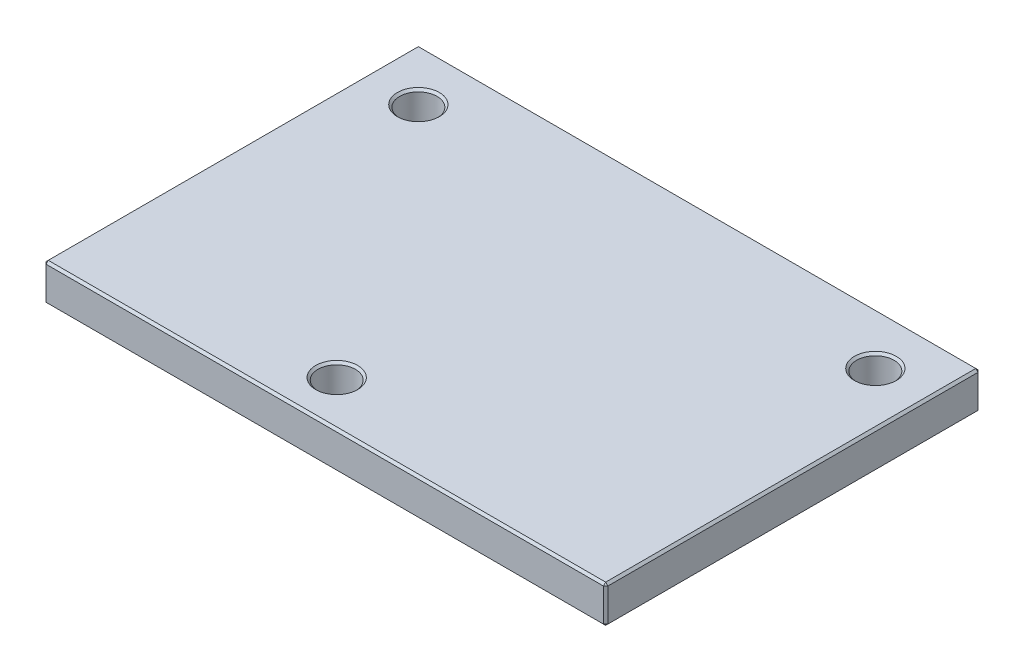
SolidWorks part; units mm, degrees
material "Plain Carbon Steel"
ref_plane "Front Plane" through (0, 0, 0) normal (0, 0, 1) x (1, 0, 0)
ref_plane "Top Plane" through (0, 0, 0) normal (0, 1, 0) x (1, 0, 0)
ref_plane "Right Plane" through (0, 0, 0) normal (1, 0, 0) x (0, 0, -1)
sketch "Sketch1" plane through (0, 0, 0) normal (0, 1, 0) x (1, 0, 0)
  line L1 (-375, -250) -> (375, -250)
  line L2 (-375, -250) -> (-375, 250)
  line L3 (-375, 250) -> (375, 250)
  line L4 (375, -250) -> (375, 250)
  line L5 (-375, -250) -> (375, 250) construction
  line L6 (-375, 250) -> (375, -250) construction
  point P0 (0, 0)
  dimension "D1" = 750
  dimension "D2" = 500
extrude "Boss-Extrude1" add sketch "Sketch1" against normal blind 50
sketch "Sketch2" plane through (0, 0, 0) normal (0, 1, 0) x (1, 0, 0)
  line L0 (375, 250) -> (-375, 250) construction
  line L1 (-375, 250) -> (-375, -250) construction
  line L2 (375, -250) -> (375, 250) construction
  line L3 (-375, -250) -> (375, -250) construction
  circle A0 centre (-305, 180) radius 25
  circle A1 centre (305, 180) radius 25
  circle A2 centre (-44, -190) radius 25
  point P8 (0, 0)
  dimension "D1" = 50
  dimension "D2" = 70
  dimension "D3" = 70
  dimension "D4" = 70
  dimension "D5" = 60
  dimension "D6" = 44
extrude "Cut-Extrude1" cut sketch "Sketch2" against normal up to next
chamfer "Chamfer1" distance 3 angle 45 6 edges at (305, -50, -205) (305, 0, -155) (-305, -50, -205) (-305, 0, -155) (-44, -50, 165) (-44, 0, 215)
chamfer "Chamfer2" distance 3 angle 45 12 edges at (0, -50, -250) (0, 0, -250) (375, -25, -250) (375, -50, 0) (375, 0, 0) (375, -25, 250) (0, -50, 250) (0, 0, 250) (-375, -25, 250) (-375, -50, 0) (-375, -25, -250) (-375, 0, 0)
